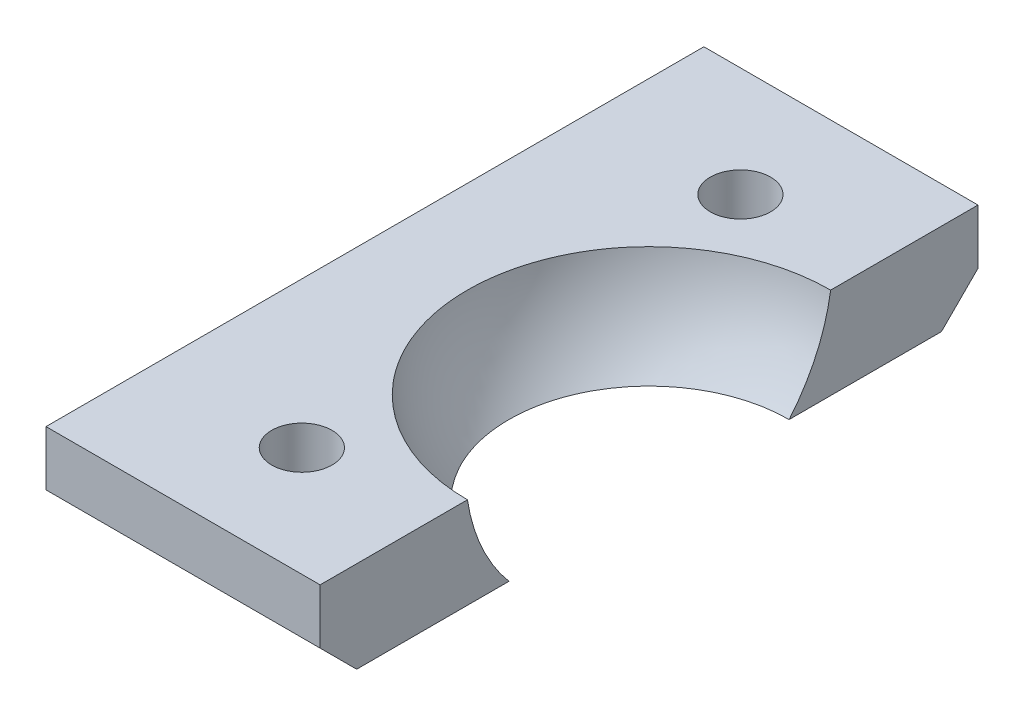
SolidWorks part; units mm, degrees
ref_plane "前视基准面" through (0, 0, 0) normal (0, 0, 1) x (1, 0, 0)
ref_plane "上视基准面" through (0, 0, 0) normal (0, 1, 0) x (1, 0, 0)
ref_plane "右视基准面" through (0, 0, 0) normal (1, 0, 0) x (0, 0, -1)
other "Configuration Table"
sketch "草图1" plane through (0, 0, 0) normal (0, 1, 0) x (1, 0, 0)
  line L1 (0, 0) -> (30, 0)
  line L2 (0, 0) -> (0, -50)
  line L3 (0, -50) -> (30, -50)
  line L4 (30, 0) -> (30, -50)
  dimension "D1" = 50
  dimension "D2" = 30
extrude "凸台-拉伸1" add sketch "草图1" along normal blind 5
ref_plane "基准面1" through (0, 6.5, 0) normal (0, 1, 0) x (1, 0, 0)
sketch "草图2" plane through (0, 6.5, 0) normal (0, 1, 0) x (1, 0, 0)
  line L0 (30, 0) -> (0, 0) construction
  line L1 (30, -50) -> (30, 0) construction
  line L2 (4.95, -25) -> (25.05, -25)
  arc A0 (4.95, -25) -> (25.05, -25) centre (15, -25) ccw
  dimension "D1" = 20.1
  dimension "D2" = 25
  dimension "D3" = 15
revolve "切除-旋转1" cut sketch "草图2" angle 360 about L2
sketch "草图3" plane through (0, 0, 0) normal (0, -1, 0) x (-1, 0, 0)
  line L0 (0, -50) -> (-30, -50) construction
  line L1 (-30, 0) -> (0, 0) construction
  line L2 (0, 0) -> (0, -50) construction
  line L3 (-30, -50) -> (-30, 0) construction
  circle A0 centre (-8, -37) radius 1.65
  circle A1 centre (-22, -37) radius 1.65
  circle A2 centre (-8, -13) radius 1.65
  circle A3 centre (-22, -13) radius 1.65
  dimension "D1" = 3.3
  dimension "D2" = 3.3
  dimension "D3" = 3.3
  dimension "D4" = 3.3
  dimension "D5" = 13
  dimension "D6" = 13
  dimension "D7" = 13
  dimension "D8" = 13
  dimension "D10" = 8
  dimension "D11" = 8
  dimension "D12" = 8
  dimension "D9" = 8
extrude "切除-拉伸1" cut sketch "草图3" against normal through all
sketch "草图4" plane through (0, 5, 0) normal (0, 1, 0) x (1, 0, 0)
  line L0 (30, 0) -> (0, 0) construction
  line L1 (-6.0841, 2.682) -> (35.1503, 2.682)
  line L2 (-6.0841, 2.682) -> (-6.0841, -7)
  line L3 (-6.0841, -7) -> (35.1503, -7)
  line L4 (35.1503, 2.682) -> (35.1503, -7)
  line L5 (-8.2466, -43) -> (39.4261, -43)
  line L6 (-8.2466, -43) -> (-8.2466, -54.0581)
  line L7 (-8.2466, -54.0581) -> (39.4261, -54.0581)
  line L8 (39.4261, -43) -> (39.4261, -54.0581)
  line L9 (0, -50) -> (30, -50) construction
  dimension "D1" = 7
  dimension "D2" = 7
extrude "切除-拉伸2" cut sketch "草图4" against normal through all
sketch "草图5" plane through (0, 5, 0) normal (0, 1, 0) x (1, 0, 0)
  line L0 (0, -7) -> (0, -43) construction
  line L1 (15, -4.8734) -> (35.5059, -4.8734)
  line L2 (15, -4.8734) -> (15, -45.2216)
  line L3 (15, -45.2216) -> (35.5059, -45.2216)
  line L4 (35.5059, -4.8734) -> (35.5059, -45.2216)
  dimension "D1" = 15
extrude "切除-拉伸3" cut sketch "草图5" against normal through all
chamfer "倒角1" distance 2 angle 45 3 edges at (7.5, 0, 7) (0, 0, 25) (7.5, 0, 43)
